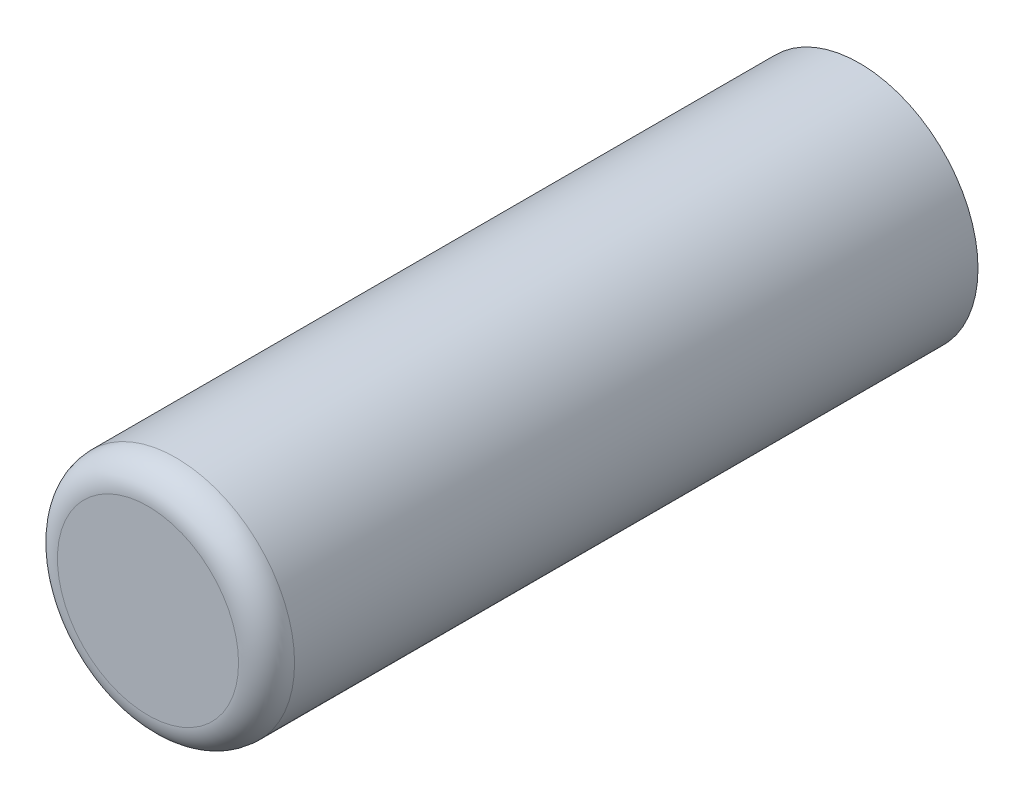
SolidWorks part; units mm, degrees
ref_plane "Front Plane" through (0, 0, 0) normal (0, 0, 1) x (1, 0, 0)
ref_plane "Top Plane" through (0, 0, 0) normal (0, 1, 0) x (1, 0, 0)
ref_plane "Right Plane" through (0, 0, 0) normal (1, 0, 0) x (0, 0, -1)
sketch "Sketch1" plane through (0, 0, 0) normal (0, 0, 1) x (1, 0, 0)
  circle A0 centre (0, 0) radius 12.7
  dimension "D1" = 25.4
extrude "Boss-Extrude1" add sketch "Sketch1" along normal blind 76.2
fillet "Fillet1" radius 3 1 edges at (12.7, 0, 76.2)
